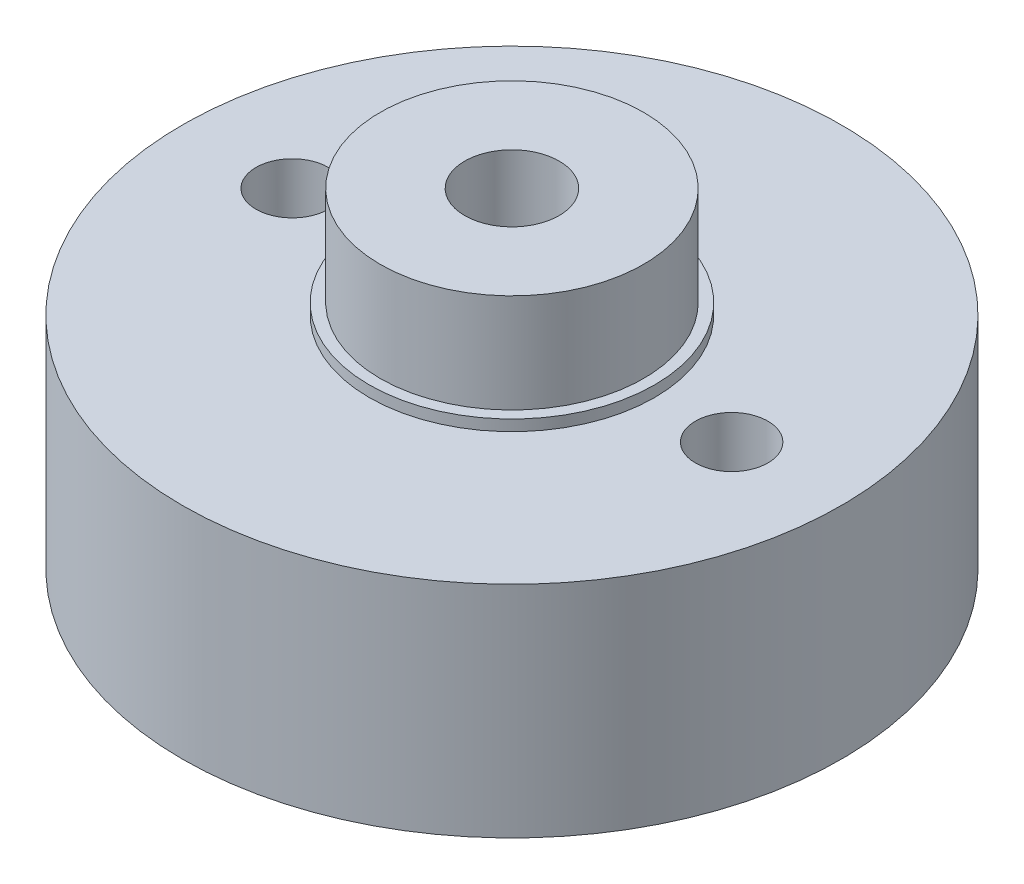
SolidWorks part; units mm, degrees
material "5052-H34"
ref_plane "正面" through (0, 0, 0) normal (0, 0, 1) x (1, 0, 0)
ref_plane "平面" through (0, 0, 0) normal (0, 1, 0) x (1, 0, 0)
ref_plane "右側面" through (0, 0, 0) normal (1, 0, 0) x (0, 0, -1)
sketch "ｽｹｯﾁ1" plane through (0, 0, 0) normal (0, 1, 0) x (1, 0, 0)
  circle A0 centre (0, 0) radius 15
  dimension "D1" = 30
extrude "ﾎﾞｽ - 押し出し1" add sketch "ｽｹｯﾁ1" along normal blind 10
sketch "ｽｹｯﾁ2" plane through (0, 10, 0) normal (0, 1, 0) x (1, 0, 0)
  circle A0 centre (0, 0) radius 5.995
  dimension "D1" = 11.99
extrude "ﾎﾞｽ - 押し出し2" add sketch "ｽｹｯﾁ2" along normal blind 5
sketch "ｽｹｯﾁ3" plane through (0, 10, 0) normal (0, 1, 0) x (1, 0, 0)
  circle A0 centre (0, 0) radius 6.495
  circle A1 centre (0, 0) radius 5.995 construction
  dimension "D1" = 0.5
extrude "ﾎﾞｽ - 押し出し3" add sketch "ｽｹｯﾁ3" along normal blind 0.5
sketch "ｽｹｯﾁ4" plane through (0, 10, 0) normal (0, 1, 0) x (1, 0, 0)
  line L0 (0, 0) -> (15, 0) construction
  line L1 (0, 0) -> (0, 15) construction
  circle A0 centre (0, 0) radius 15 construction
  circle A1 centre (10, 0) radius 1.65
  circle A2 centre (-10, 0) radius 1.65
  dimension "D1" = 3.3
  dimension "D2" = 20
extrude "ｶｯﾄ - 押し出し1" cut sketch "ｽｹｯﾁ4" against normal up to surface (10 mm away) up to face at (0, 0, 15)
sketch "ｽｹｯﾁ5" plane through (0, 15, 0) normal (0, 1, 0) x (1, 0, 0)
  circle A0 centre (0, 0) radius 2.15
  dimension "D1" = 4.3
extrude "ｶｯﾄ - 押し出し2" cut sketch "ｽｹｯﾁ5" against normal up to surface (15 mm away) up to face at (10, 0, 1.65)
